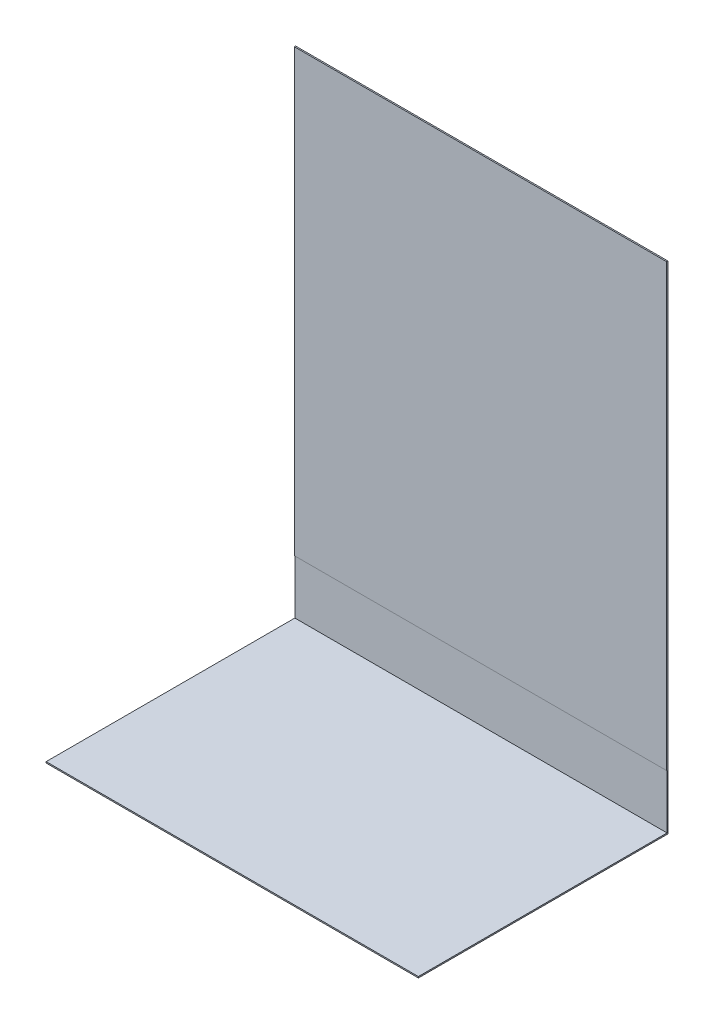
SolidWorks part; units mm, degrees
ref_plane "Front Plane" through (0, 0, 0) normal (0, 0, 1) x (1, 0, 0)
ref_plane "Top Plane" through (0, 0, 0) normal (0, 1, 0) x (1, 0, 0)
ref_plane "Right Plane" through (0, 0, 0) normal (1, 0, 0) x (0, 0, -1)
sketch "Sketch1" plane through (0, 0, 0) normal (0, 0, 1) x (1, 0, 0)
  line L1 (-914.4, 1219.2) -> (914.4, 1219.2)
  line L2 (-914.4, 1219.2) -> (-914.4, -1219.2)
  line L3 (-914.4, -1219.2) -> (914.4, -1219.2)
  line L4 (914.4, 1219.2) -> (914.4, -1219.2)
  line L5 (-914.4, 1219.2) -> (914.4, -1219.2) construction
  line L6 (-914.4, -1219.2) -> (914.4, 1219.2) construction
  point P0 (0, 0)
  dimension "D1" = 1828.8
  dimension "D2" = 2438.4
extrude "Boss-Extrude1" add sketch "Sketch1" along normal blind 6.35
sketch "Sketch2" plane through (0, 0, 6.35) normal (0, 0, 1) x (1, 0, 0)
  line L0 (914.4, -1219.2) -> (914.4, 1219.2) construction
  line L1 (-914.4, -1219.2) -> (914.4, -1219.2)
  line L2 (-914.4, -1219.2) -> (-914.4, -1212.85)
  line L3 (-914.4, -1212.85) -> (914.4, -1212.85)
  line L4 (914.4, -1219.2) -> (914.4, -1212.85)
  dimension "D1" = 6.35
extrude "Boss-Extrude2" add sketch "Sketch2" along normal blind 1219.2
sketch "Sketch3" plane through (0, 0, 6.35) normal (0, 0, 1) x (1, 0, 0)
  line L0 (914.4, -1212.85) -> (914.4, 1219.2) construction
  line L1 (-914.4, -1212.85) -> (914.4, -1212.85)
  line L2 (-914.4, -1212.85) -> (-914.4, -946.15)
  line L3 (-914.4, -946.15) -> (914.4, -946.15)
  line L4 (914.4, -1212.85) -> (914.4, -946.15)
  dimension "D1" = 266.7
extrude "Cut-Extrude1" cut sketch "Sketch3" against normal blind 2.54
